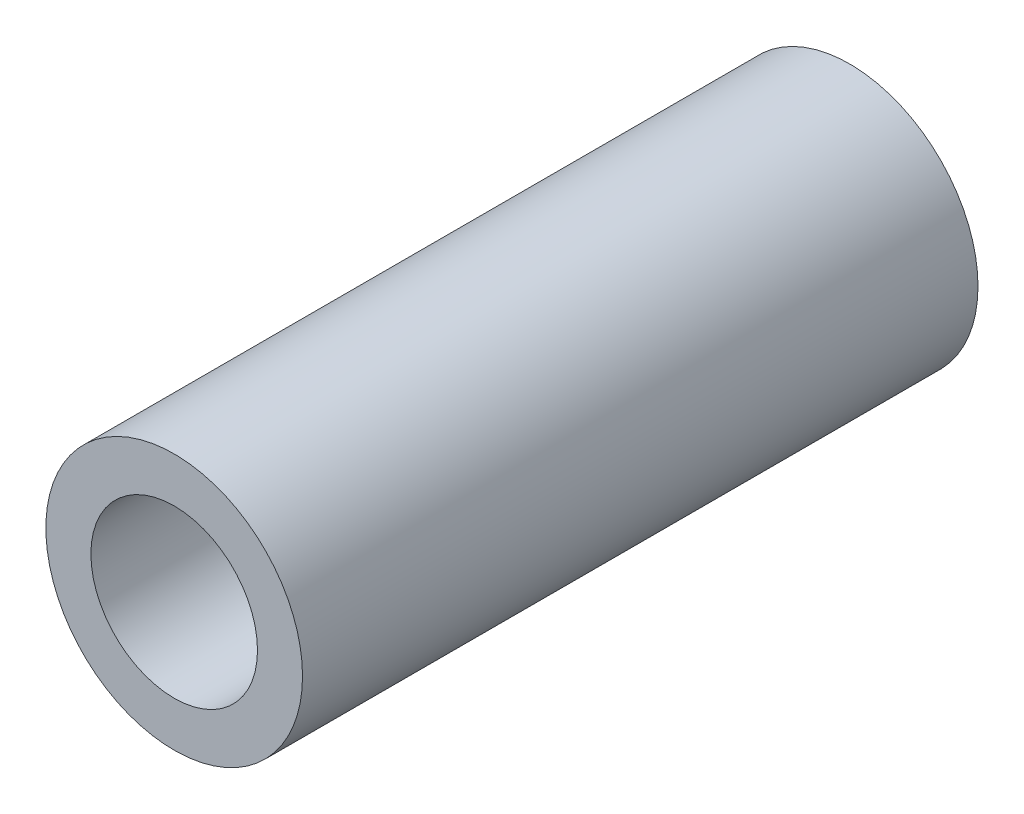
SolidWorks part; units mm, degrees
ref_plane "Спереди" through (0, 0, 0) normal (0, 0, 1) x (1, 0, 0)
ref_plane "Сверху" through (0, 0, 0) normal (0, 1, 0) x (1, 0, 0)
ref_plane "Справа" through (0, 0, 0) normal (1, 0, 0) x (0, 0, -1)
sketch "Эскиз1" plane through (0, 0, 0) normal (0, 0, 1) x (1, 0, 0)
  circle A0 centre (0, 0) radius 1.85
  circle A1 centre (0, 0) radius 2.85
  dimension "D1" = 3.7
  dimension "D2" = 5.7
extrude "Бобышка-Вытянуть1" add sketch "Эскиз1" along normal blind 15
